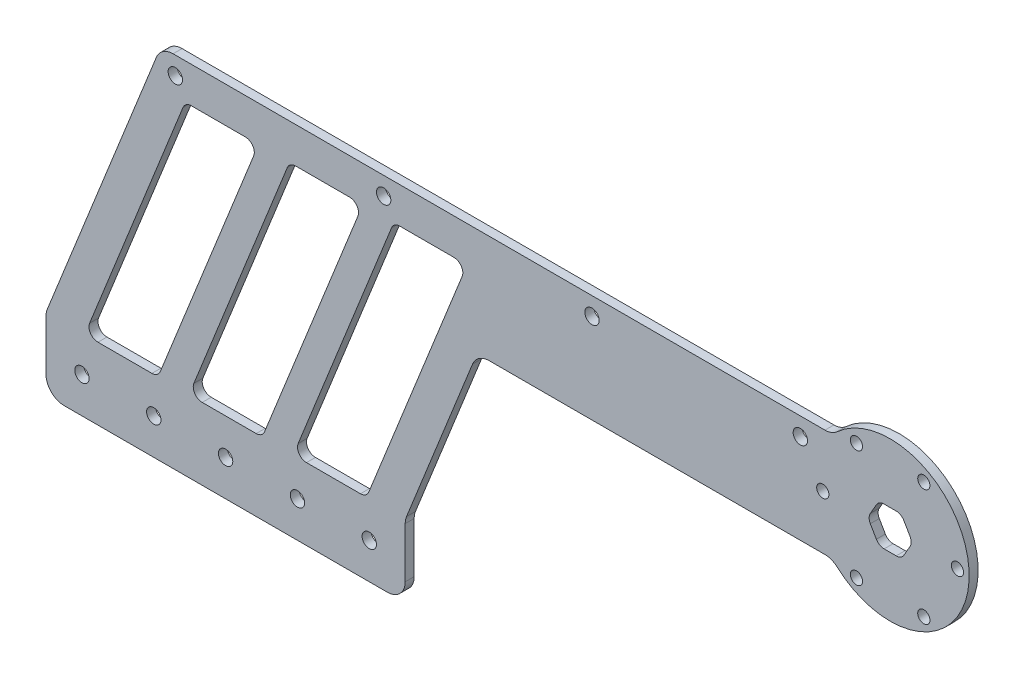
SolidWorks part; units mm, degrees
material "6061-T6 (SS)"
ref_plane "Front Plane" through (0, 0, 0) normal (0, 0, 1) x (1, 0, 0)
ref_plane "Top Plane" through (0, 0, 0) normal (0, 1, 0) x (1, 0, 0)
ref_plane "Right Plane" through (0, 0, 0) normal (1, 0, 0) x (0, 0, -1)
sketch "Sketch1" plane through (0, 0, 0) normal (0, 0, 1) x (1, 0, 0)
  line L0 (0, 25.4) -> (0, 0)
  line L1 (0, 0) -> (317.5, 0) construction
  line L2 (317.5, 0) -> (317.5, 25.4) construction
  line L3 (317.5, 25.4) -> (317.5, 127) construction
  line L4 (317.5, 127) -> (279.4, 127)
  line L5 (279.4, 127) -> (0, 25.4) construction
  line L6 (317.5, 127) -> (152.4, 127) construction
  line L7 (302.4095, 101.092) -> (306.3689, 107.95)
  line L8 (306.3689, 107.95) -> (302.4095, 114.808)
  line L9 (302.4095, 114.808) -> (294.4905, 114.808)
  line L10 (294.4905, 114.808) -> (290.5311, 107.95)
  line L11 (290.5311, 107.95) -> (294.4905, 101.092)
  line L12 (294.4905, 101.092) -> (302.4095, 101.092)
  line L13 (279.4, 127) -> (317.5, 127) construction
  line L14 (279.4, 127) -> (279.4, 88.9) construction
  line L15 (279.4, 88.9) -> (317.5, 88.9) construction
  line L16 (317.5, 127) -> (317.5, 88.9) construction
  line L17 (279.4, 127) -> (317.5, 88.9) construction
  line L18 (279.4, 88.9) -> (317.5, 127) construction
  line L19 (317.5, 88.9) -> (152.4, 88.9)
  line L21 (127, 0) -> (0, 0)
  line L22 (0, 25.4) -> (0, 127) construction
  line L23 (0, 127) -> (152.4, 127) construction
  line L24 (279.4, 127) -> (152.4, 127)
  line L25 (317.5, 88.9) -> (317.5, 127)
  line L26 (0, 25.4) -> (40.64, 127)
  line L27 (40.64, 127) -> (152.4, 127)
  line L28 (127, 0) -> (127, 25.4)
  line L29 (127, 25.4) -> (152.4, 88.9)
  line L30 (292.5108, 111.379) -> (304.3892, 104.521) construction
  line L31 (298.45, 107.95) -> (274.6375, 107.95) construction
  line L32 (298.45, 107.95) -> (286.5437, 128.5722) construction
  circle A1 centre (298.45, 107.95) radius 6.858 construction
  circle A2 centre (12.7, 12.7) radius 2.54
  circle A3 centre (38.1, 12.7) radius 2.54
  circle A4 centre (63.5, 12.7) radius 2.54
  circle A5 centre (88.9, 12.7) radius 2.54
  circle A6 centre (114.3, 12.7) radius 2.54
  circle A7 centre (298.45, 107.95) radius 23.8125 construction
  circle A8 centre (274.6375, 107.95) radius 2.159
  circle A11 centre (298.45, 107.95) radius 27.94
  circle A12 centre (286.5437, 128.5722) radius 2.159
  circle A13 centre (310.3562, 128.5722) radius 2.159
  circle A14 centre (322.2625, 107.95) radius 2.159
  circle A15 centre (310.3562, 87.3278) radius 2.159
  circle A16 centre (286.5437, 87.3278) radius 2.159
  point P16 (298.45, 127)
  point P20 (298.45, 107.95)
  point P21 (0, 12.7)
  point P47 (304.3892, 104.521)
  dimension "D4" = 13.716
  dimension "D6" = 5.08
  dimension "D10" = 47.625
  dimension "D11" = 6
  dimension "D15" = 60
  dimension "D12" = 55.88
  dimension "D16" = 4.318
  dimension "D1" = 25.4
  dimension "D2" = 152.4
  dimension "D3" = 38.1
  dimension "D5" = 101.6
  dimension "D7" = 12.7
  dimension "D9" = 25.4
  dimension "D13" = 165.1
  dimension "D14" = 127
  dimension "D8" = 5
extrude "Boss-Extrude1" add sketch "Sketch1" along normal blind 3.175 contours A11 L24 L27 L26 L0 L21 L28 L29 L19 A4 A3 A2 | A16 L19 A15 L25 L4 A13 A12 L24 A11 L12 L11 L10 L9 L8 L7 A8 | A16 L19 A11 L24 L4 A12 A13 L25 A15 A14
fillet "Fillet1" radius 6.35 8 edges at (40.64, 127, 1.5875) (152.4, 88.9, 1.5875) (127, 0, 1.5875) (0, 0, 1.5875) (0, 25.4, 1.5875) (127, 25.4, 1.5875) (278.0113, 127, 1.5875) (278.0113, 88.9, 1.5875)
sketch "Sketch2" plane through (0, 0, 3.175) normal (0, 0, 1) x (1, 0, 0)
  line L0 (120.65, 0) -> (6.35, 0) construction
  line L8 (13.6783, 25.4) -> (114.3393, 25.4)
  line L10 (45.069, 25.4) -> (80.629, 114.3)
  line L11 (81.931, 25.4) -> (117.491, 114.3)
  line L12 (30.9692, 68.6271) -> (56.8885, 68.6271) construction
  line L13 (67.8312, 68.6271) -> (93.7505, 68.6271) construction
  line L14 (49.562, 22.9542) -> (86.1003, 114.3)
  line L15 (86.424, 22.9542) -> (122.9623, 114.3)
  line L24 (304.8, 114.3) -> (49.2383, 114.3)
  line L25 (49.2383, 114.3) -> (12.7, 22.9542)
  line L26 (12.7, 22.9542) -> (12.7, 12.7)
  line L27 (12.7, 12.7) -> (114.3, 12.7)
  line L28 (114.3, 12.7) -> (114.3, 24.1771)
  line L29 (115.6625, 31.2521) -> (139.0117, 89.625)
  line L30 (156.6992, 101.6) -> (304.8, 101.6)
  line L31 (304.8, 101.6) -> (304.8, 114.3)
  line L32 (39.5977, 25.4) -> (75.9123, 116.1867)
  line L33 (76.4597, 25.4) -> (112.7743, 116.1867)
  line L34 (49.7857, 23.5133) -> (85.3457, 112.4133) construction
  line L35 (86.6477, 23.5133) -> (122.2077, 112.4133) construction
  line L36 (77.2143, 27.2867) -> (112.7743, 116.1867) construction
  line L37 (40.3523, 27.2867) -> (75.9123, 116.1867) construction
  line L38 (104.6932, 68.6271) -> (130.6125, 68.6271) construction
  line L39 (139.0117, 89.625) -> (148.8817, 114.3)
  line L40 (115.6625, 31.2521) -> (111.7098, 21.3703)
  arc A18 (115.6625, 31.2521) -> (114.3, 24.1771) centre (133.35, 24.1771) ccw
  arc A19 (156.6992, 101.6) -> (139.0117, 89.625) centre (156.6992, 82.55) ccw
  dimension "D1" = 19.05
  dimension "D2" = 25.4
  dimension "D5" = 12.7
  dimension "D6" = 13.6783
  dimension "D7" = 39.5977
  dimension "D8" = 45.069
  dimension "D9" = 49.2383
  dimension "D10" = 111.7098
  dimension "D11" = 114.3
  dimension "D12" = 114.3393
  dimension "D13" = 139.0117
  dimension "D14" = 304.8
  dimension "D15" = 12.7
  dimension "D3" = 5.08
  dimension "D4" = 5.08
extrude "Cut-Extrude1" cut sketch "Sketch2" against normal through all contours L8 L32 L24 L25 | L8 L33 L24 L14 | A18 L29 L39 L24 L15 L8
fillet "Fillet2" radius 3.175 12 edges at (13.6783, 25.4, 1.5875) (49.2383, 114.3, 1.5875) (75.1577, 114.3, 1.5875) (39.5977, 25.4, 1.5875) (50.5403, 25.4, 1.5875) (86.1003, 114.3, 1.5875) (112.0197, 114.3, 1.5875) (76.4597, 25.4, 1.5875) (87.4023, 25.4, 1.5875) (122.9623, 114.3, 1.5875) (148.8817, 114.3, 1.5875) (113.3217, 25.4, 1.5875)
sketch "Sketch3" plane through (0, 0, 3.175) normal (0, 0, 1) x (1, 0, 0)
  line L0 (38.1, 120.65) -> (323.3368, 120.65) construction
  line L3 (70.4681, 114.3) -> (70.4681, 127) construction
  line L5 (275.4143, 127) -> (44.9392, 127) construction
  line L6 (70.4681, 114.3) -> (51.3879, 114.3) construction
  line L7 (0.4542, 26.5354) -> (39.0433, 123.0083) construction
  circle A0 centre (45.72, 120.65) radius 2.54
  circle A1 centre (82.55, 120.65) radius 2.54 construction
  circle A2 centre (119.38, 120.65) radius 2.54
  circle A3 centre (156.21, 120.65) radius 2.54 construction
  circle A4 centre (193.04, 120.65) radius 2.54
  circle A5 centre (229.87, 120.65) radius 2.54 construction
  circle A6 centre (266.7, 120.65) radius 2.54
  arc A7 (279.6802, 87.2537) -> (279.6802, 128.6463) centre (298.45, 107.95) ccw construction
  point P13 (70.4681, 120.65)
  dimension "D1" = 5.08
  dimension "D2" = 7
  dimension "D3" = 36.83
  dimension "D4" = 7.62
extrude "Cut-Extrude2" cut sketch "Sketch3" against normal through all
fillet "Fillet3" radius 3.175 6 edges at (302.4095, 101.092, 1.5875) (306.3689, 107.95, 1.5875) (302.4095, 114.808, 1.5875) (290.5311, 107.95, 1.5875) (294.4905, 101.092, 1.5875) (294.4905, 114.808, 1.5875)
sketch "Sketch4" plane through (0, 0, 0) normal (0, 0, 1) x (1, 0, 0)
  line L0 (-12.7, -6.8773) -> (-12.7, 49993.1227) construction
  line L1 (-12.7, -12.7) -> (49987.3, -12.7) construction
  line L4 (0, 24.1771) -> (0, 6.35) construction
  line L5 (120.65, 0) -> (6.35, 0) construction
  line L8 (106.6288, 41.5756) -> (69.7988, 41.5756) construction
  line L13 (139.5025, 107.95) -> (127.2615, 107.95)
  line L14 (127.2615, 107.95) -> (96.7815, 31.75)
  line L15 (96.7815, 31.75) -> (109.0225, 31.75)
  line L16 (109.0225, 31.75) -> (139.5025, 107.95)
  line L17 (139.5025, 107.95) -> (127.2615, 107.95) construction
  line L18 (127.2615, 107.95) -> (96.7815, 31.75) construction
  line L19 (96.7815, 31.75) -> (109.0225, 31.75) construction
  line L20 (109.0225, 31.75) -> (139.5025, 107.95) construction
  line L21 (34.5002, 29.7542) -> (67.5202, 112.3042)
  line L22 (34.5002, 29.7542) -> (67.5202, 112.3042) construction
  circle A0 centre (106.6288, 41.5756) radius 3.175
  circle A1 centre (129.8673, 98.0509) radius 3.175
  circle A10 centre (69.7988, 41.5756) radius 3.175
  circle A11 centre (93.0373, 98.0509) radius 3.175
  circle A12 centre (32.9688, 41.5756) radius 3.175
  circle A13 centre (56.2073, 98.0509) radius 3.175
  point P4 (-12.7, -12.7)
  dimension "D3" = 6.35
  dimension "D1" = 12.7
  dimension "D2" = 12.7
  dimension "D6" = 36.83
  dimension "D4" = 6.35
  dimension "D7" = 6.35
  dimension "D5" = 3
